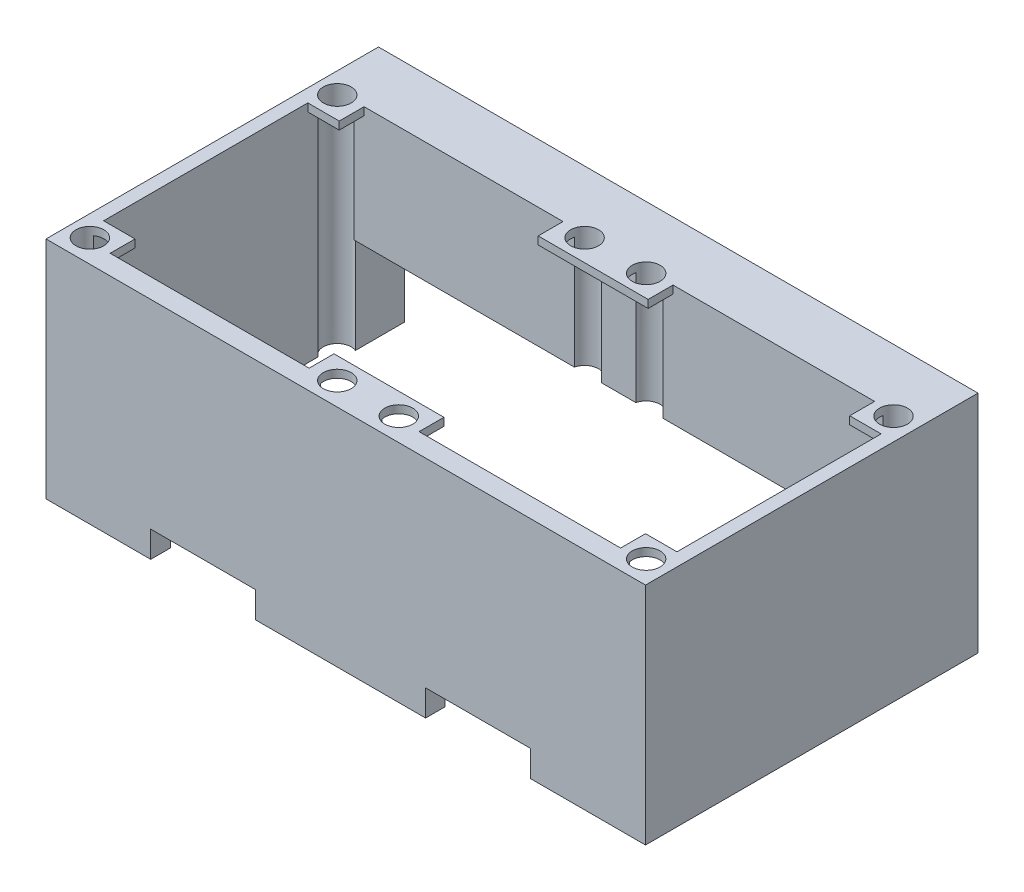
SolidWorks part; units mm, degrees
ref_plane "Front Plane" through (0, 0, 0) normal (0, 0, 1) x (1, 0, 0)
ref_plane "Top Plane" through (0, 0, 0) normal (0, 1, 0) x (1, 0, 0)
ref_plane "Right Plane" through (0, 0, 0) normal (1, 0, 0) x (0, 0, -1)
sketch "Sketch1" plane through (0, 0, 0) normal (0, 1, 0) x (1, 0, 0)
  line L1 (-29.083, -14.224) -> (29.083, -14.224)
  line L2 (-29.083, -14.224) -> (-29.083, 14.224)
  line L3 (-29.083, 14.224) -> (29.083, 14.224)
  line L4 (29.083, -14.224) -> (29.083, 14.224)
  line L5 (-29.083, -14.224) -> (29.083, 14.224) construction
  line L6 (-29.083, 14.224) -> (29.083, -14.224) construction
  point P0 (0, 0)
  dimension "D1" = 58.166
  dimension "D2" = 28.448
extrude "Boss-Extrude1" add sketch "Sketch1" along normal blind 21.844
sketch "Sketch2" plane through (0, 21.844, 0) normal (0, 1, 0) x (1, 0, 0)
  line L0 (29.083, 14.224) -> (-29.083, 14.224) construction
  line L1 (-27.813, 12.319) -> (27.813, 12.319)
  line L2 (-27.813, 12.319) -> (-27.813, -12.319)
  line L3 (-27.813, -12.319) -> (27.813, -12.319)
  line L4 (27.813, 12.319) -> (27.813, -12.319)
  line L5 (29.083, -14.224) -> (29.083, 14.224) construction
  line L6 (-29.083, 14.224) -> (-29.083, -14.224) construction
  line L7 (-29.083, -14.224) -> (29.083, -14.224) construction
  dimension "D1" = 1.905
  dimension "D2" = 1.905
  dimension "D3" = 1.27
  dimension "D4" = 1.27
extrude "Cut-Extrude1" cut sketch "Sketch2" against normal through all
sketch "Sketch3" plane through (0, 21.844, 0) normal (0, 1, 0) x (1, 0, 0)
  line L0 (27.813, 12.319) -> (-27.813, 12.319) construction
  line L1 (-27.813, 12.319) -> (-24.765, 12.319)
  line L2 (-27.813, 12.319) -> (-27.813, 9.906)
  line L3 (-27.813, 9.906) -> (-24.765, 9.906)
  line L4 (-24.765, 12.319) -> (-24.765, 9.906)
  line L5 (-27.813, -12.319) -> (-24.765, -12.319)
  line L6 (-27.813, -12.319) -> (-27.813, -9.906)
  line L7 (-27.813, -9.906) -> (-24.765, -9.906)
  line L8 (-24.765, -12.319) -> (-24.765, -9.906)
  line L9 (27.813, 12.319) -> (24.765, 12.319)
  line L10 (27.813, 12.319) -> (27.813, 9.906)
  line L11 (27.813, 9.906) -> (24.765, 9.906)
  line L12 (24.765, 12.319) -> (24.765, 9.906)
  line L13 (27.813, -12.319) -> (24.765, -12.319)
  line L14 (27.813, -12.319) -> (27.813, -9.906)
  line L15 (27.813, -9.906) -> (24.765, -9.906)
  line L16 (24.765, -12.319) -> (24.765, -9.906)
  line L17 (-5.461, 12.319) -> (5.207, 12.319)
  line L18 (-5.461, 12.319) -> (-5.461, 9.906)
  line L19 (-5.461, 9.906) -> (5.207, 9.906)
  line L20 (5.207, 12.319) -> (5.207, 9.906)
  line L21 (-27.813, -12.319) -> (27.813, -12.319) construction
  line L22 (-5.461, -12.319) -> (5.207, -12.319)
  line L23 (-5.461, -12.319) -> (-5.461, -9.906)
  line L24 (-5.461, -9.906) -> (5.207, -9.906)
  line L25 (5.207, -12.319) -> (5.207, -9.906)
  line L26 (-29.083, 14.224) -> (-29.083, -14.224) construction
  line L27 (29.083, 14.224) -> (-29.083, 14.224) construction
  dimension "D1" = 4.318
  dimension "D2" = 4.318
  dimension "D3" = 10.668
  dimension "D4" = 19.304
  dimension "D5" = 19.304
extrude "Boss-Extrude2" add sketch "Sketch3" against normal blind 0.762
hole_wizard "#2 Clearance Hole1" positions "Sketch5" profile "Sketch4" hole size "#2" standard "ANSI Inch" end condition through all
sketch "Sketch5" plane through (0, 21.844, 0) normal (0, 1, 0) x (1, 0, 0)
  line L0 (-27.051, 12.0015) -> (-3.0505, 12.0015) construction
  line L1 (-27.051, 12.0015) -> (-27.051, -11.999) construction
  line L2 (2.9185, -11.999) -> (26.9189, -11.999) construction
  line L3 (2.9185, -11.999) -> (2.9185, 12.0015) construction
  line L4 (-29.083, 14.224) -> (-29.083, -14.224) construction
  line L7 (29.083, 14.224) -> (-29.083, 14.224) construction
  line L9 (-29.083, -14.224) -> (29.083, -14.224) construction
  point P0 (-27.051, 12.0015)
  point P10 (-3.0505, 12.0015)
  point P11 (-3.0505, -11.999)
  point P12 (-27.051, -11.999)
  point P16 (2.9185, -11.999)
  point P23 (26.9189, -11.999)
  point P24 (26.9189, 12.0015)
  point P25 (2.9185, 12.0015)
  dimension "D3" = 24.0005
  dimension "D4" = 24.0005
  dimension "D7" = 24.0005
  dimension "D8" = 24.0005
  dimension "D9" = 2.032
  dimension "D10" = 2.2225
  dimension "D11" = 2.2225
  dimension "D12" = 5.969
  dimension "D1" = 2
  dimension "D2" = 2
  dimension "D5" = 2
  dimension "D6" = 2
sketch "Sketch4" plane through (-27.051, 21.844, -12.0015) normal (1, 0, 0) x (0, 0, 1)
  line L0 (0, 0) -> (0, 21.844)
  line L1 (0, 21.844) -> (1.3525, 21.844)
  line L2 (1.3525, 21.844) -> (1.3525, 0)
  line L5 (1.3525, 0) -> (0, 0)
  line L11 (0, -6.35) -> (0, 107.95) construction
  dimension "Thru Hole Dia." = 2.7051
  dimension "Thru Hole Depth" = 21.844
sketch "Sketch6" plane through (0, 0, 14.224) normal (0, 0, 1) x (1, 0, 0)
  line L0 (-29.083, 0) -> (29.083, 0) construction
  line L1 (-18.923, 0) -> (-8.763, 0)
  line L2 (-18.923, 0) -> (-18.923, 2.54)
  line L3 (-18.923, 2.54) -> (-8.763, 2.54)
  line L4 (-8.763, 0) -> (-8.763, 2.54)
  line L5 (-29.083, 21.844) -> (-29.083, 0) construction
  line L6 (7.747, 0) -> (17.907, 0)
  line L7 (7.747, 0) -> (7.747, 2.54)
  line L8 (7.747, 2.54) -> (17.907, 2.54)
  line L9 (17.907, 0) -> (17.907, 2.54)
  dimension "D1" = 10.16
  dimension "D2" = 10.16
  dimension "D3" = 2.54
  dimension "D4" = 16.51
  dimension "D5" = 10.16
  dimension "D6" = 2.54
extrude "Cut-Extrude2" cut sketch "Sketch6" against normal up to next
sketch "Sketch7" plane through (0, 0, -14.224) normal (0, 0, -1) x (-1, 0, 0)
  line L1 (-29.083, 0) -> (29.083, 0)
  line L2 (-29.083, 0) -> (-29.083, 21.844)
  line L3 (-29.083, 21.844) -> (29.083, 21.844)
  line L4 (29.083, 0) -> (29.083, 21.844)
extrude "Boss-Extrude3" add sketch "Sketch7" along normal blind 3.81
sketch "Sketch8" plane through (0, 0, -18.034) normal (0, 0, -1) x (-1, 0, 0)
  line L0 (-29.083, 0) -> (29.083, 0) construction
  line L1 (-26.543, 0) -> (26.543, 0)
  line L2 (-26.543, 0) -> (-26.543, 10.16)
  line L3 (-26.543, 10.16) -> (26.543, 10.16)
  line L4 (26.543, 0) -> (26.543, 10.16)
  line L5 (29.083, 0) -> (29.083, 21.844) construction
  line L6 (-29.083, 21.844) -> (-29.083, 0) construction
  dimension "D1" = 10.16
  dimension "D2" = 2.54
  dimension "D3" = 2.54
extrude "Cut-Extrude3" cut sketch "Sketch8" against normal up to next
equation "\"D1@Boss-Extrude3\"=1.27-\"D2@Sketch1\""
